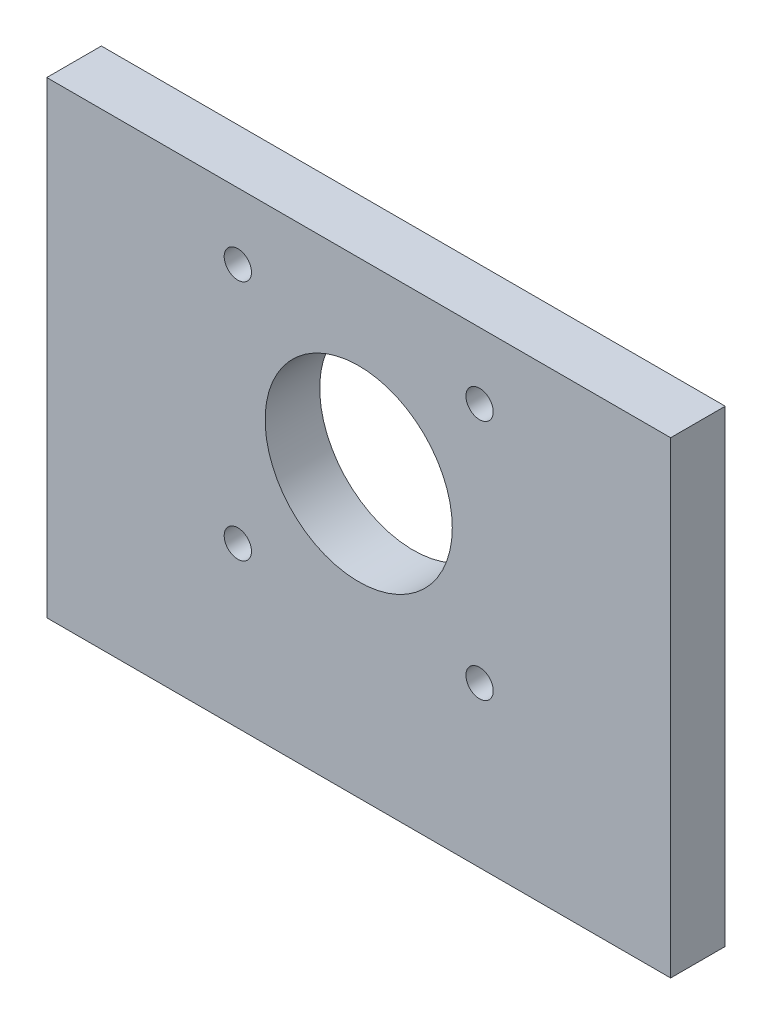
SolidWorks part; units mm, degrees
ref_plane "前视基准面" through (0, 0, 0) normal (0, 0, 1) x (1, 0, 0)
ref_plane "上视基准面" through (0, 0, 0) normal (0, 1, 0) x (1, 0, 0)
ref_plane "右视基准面" through (0, 0, 0) normal (1, 0, 0) x (0, 0, -1)
other "Configuration Table"
sketch "外形与孔位_z_motor_mount" plane through (0, 0, 0) normal (0, 0, 1) x (1, 0, 0)
  line L0 (0, 0) -> (80, 0)
  line L1 (80, 0) -> (80, 60)
  line L2 (80, 60) -> (0, 60)
  line L3 (0, 60) -> (0, 0)
  circle A0 centre (40, 36) radius 12
  circle A1 centre (24.5, 20.5) radius 1.75
  circle A2 centre (24.5, 51.5) radius 1.75
  circle A3 centre (55.5, 20.5) radius 1.75
  circle A4 centre (55.5, 51.5) radius 1.75
extrude "板厚_7mm" add sketch "外形与孔位_z_motor_mount" along normal blind 7
